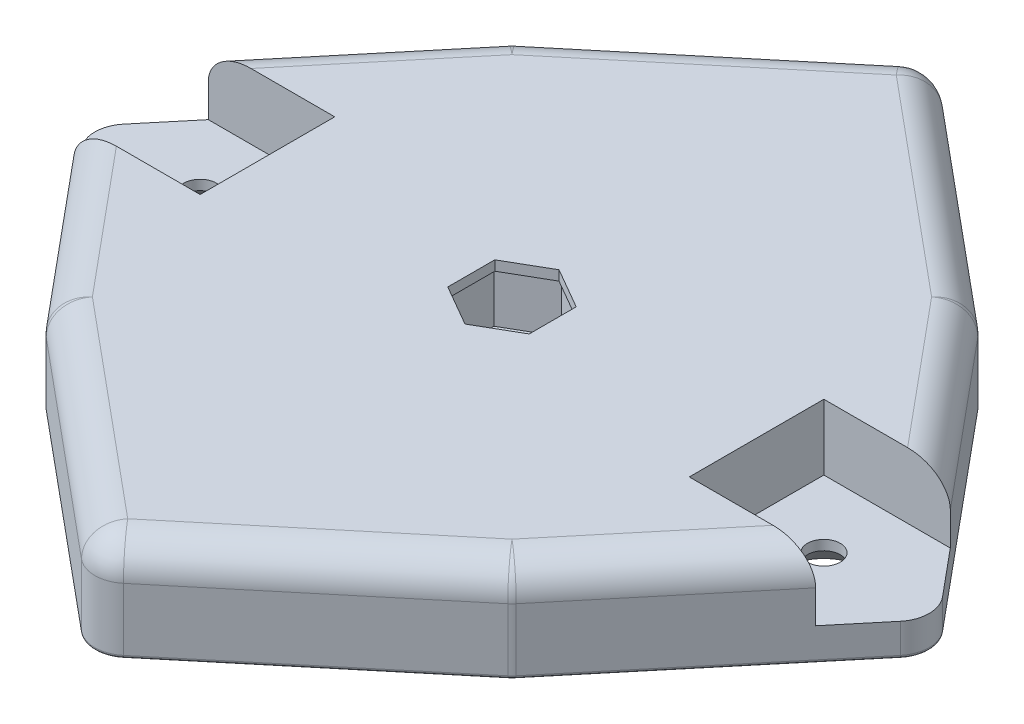
SolidWorks part; units mm, degrees
ref_plane "Front" through (0, 0, 0) normal (0, 0, 1) x (1, 0, 0)
ref_plane "Top" through (0, 0, 0) normal (0, 1, 0) x (1, 0, 0)
ref_plane "Right" through (0, 0, 0) normal (1, 0, 0) x (0, 0, -1)
sketch "Esquisse1" plane through (0, 0, 0) normal (0, 1, 0) x (1, 0, 0)
  line L0 (-47.5, 0) -> (47.5, 0) construction
  line L5 (-65.0329, 0) -> (0, -78.1935)
  line L6 (-65.0329, 0) -> (0, 78.1935)
  line L7 (0, -78.1935) -> (65.0329, 0)
  line L8 (0, 78.1935) -> (65.0329, 0)
  circle A0 centre (0, 0) radius 4.5
  circle A1 centre (-47.5, 0) radius 2.5
  circle A2 centre (47.5, 0) radius 2.5
  point P48 (0, 0)
  dimension "D1" = 9
  dimension "D3" = 5
  dimension "D5" = 100
  dimension "D2" = 100
  dimension "D4" = 95
  dimension "D6" = 100.5
extrude "Boss.-Extru.1" add sketch "Esquisse1" along normal blind 15
sketch "Esquisse2" plane through (0, 15, 0) normal (0, 1, 0) x (1, 0, 0)
  line L0 (0, 65.0329) -> (-78.1935, 0)
  line L1 (-78.1935, 0) -> (0, -65.0329)
  line L2 (0, -65.0329) -> (78.1935, 0)
  line L3 (78.1935, 0) -> (0, 65.0329)
  line L4 (-78.1935, 0) -> (78.1935, 0) construction
  line L5 (65.0329, 0) -> (0, 78.1935) construction
  dimension "D1" = 100.5
extrude "Enlèv. mat.-Extru.1" cut sketch "Esquisse2" against normal through all flip side to cut
fillet "Congé1" radius 5 8 edges at (0, 7.5, 65.0329) (-35.5043, 7.5, 35.5043) (-35.5043, 7.5, -35.5043) (0, 7.5, -65.0329) (35.5043, 7.5, -35.5043) (65.0329, 7.5, 0) (35.5043, 7.5, 35.5043) (-65.0329, 7.5, 0)
sketch "Esquisse3" plane through (0, 15, 0) normal (0, 1, 0) x (1, 0, 0)
  line L0 (0, -50) -> (0, 50) construction
  line L1 (-63.5296, 10.25) -> (-37.25, 10.25)
  line L3 (-63.5296, -10.25) -> (-37.25, -10.25)
  line L4 (-37.25, 10.25) -> (-37.25, -10.25)
  line L5 (-47.5, -10.25) -> (-47.5, 10.25) construction
  line L6 (-63.5296, 0) -> (-37.25, 0) construction
  line L8 (-63.5296, 10.25) -> (-63.5296, -10.25)
  line L9 (63.5296, 10.25) -> (63.5296, -10.25)
  line L27 (37.25, 10.25) -> (37.25, -10.25)
  line L28 (63.5296, -10.25) -> (37.25, -10.25)
  line L29 (63.5296, 10.25) -> (37.25, 10.25)
  circle A3 centre (-47.5, 0) radius 2.5 construction
  arc A4 (-62.3738, 3.1972) -> (-62.3738, -3.1972) centre (-58.5296, 0) ccw construction
  point P0 (0, 0)
  point P49 (47.5, 0)
  point P91 (-47.5, 0)
  dimension "D2" = 20.5
  dimension "D3" = 10.25
sketch "Esquisse4" plane through (0, 15, 0) normal (0, 1, 0) x (1, 0, 0)
  line L1 (6.5, 3.7528) -> (0, 7.5056)
  line L2 (0, 7.5056) -> (-6.5, 3.7528)
  line L3 (-6.5, 3.7528) -> (-6.5, -3.7528)
  line L4 (-6.5, -3.7528) -> (0, -7.5056)
  line L5 (0, -7.5056) -> (6.5, -3.7528)
  line L6 (6.5, -3.7528) -> (6.5, 3.7528)
  circle A0 centre (0, 0) radius 6.5 construction
  dimension "D1" = 13
extrude "Enlèv. mat.-Extru.2" cut sketch "Esquisse4" against normal blind 9
extrude "Enlèv. mat.-Extru.3" cut sketch "Esquisse3" against normal offset from surface (10 mm away) 5 up to face at (-47.5, 0, 2.5)
fillet "Congé2" radius 5 14 edges at (46.1531, 15, -22.7005) (35.4894, 15, -35.4894) (19.1741, 15, -49.0859) (0, 15, -63.5296) (-19.1741, 15, -49.0859) (-35.4894, 15, -35.4894) (46.1531, 15, 22.7005) (35.4894, 15, 35.4894) (19.1741, 15, 49.0859) (0, 15, 63.5296) (-19.1741, 15, 49.0859) (-35.4894, 15, 35.4894) (-46.1531, 15, -22.7005) (-46.1531, 15, 22.7005)
fillet "Congé3" radius 0.5 16 edges at (-63.5296, 0, 0) (-49.0859, 0, -19.1741) (-35.4894, 0, -35.4894) (-19.1741, 0, -49.0859) (0, 0, -63.5296) (19.1741, 0, -49.0859) (35.4894, 0, -35.4894) (49.0859, 0, -19.1741) (63.5296, 0, 0) (49.0859, 0, 19.1741) (35.4894, 0, 35.4894) (19.1741, 0, 49.0859) (0, 0, 63.5296) (-19.1741, 0, 49.0859) (-35.4894, 0, 35.4894) (-49.0859, 0, 19.1741)
sketch "Esquisse5" plane through (0, 15, 0) normal (0, 1, 0) x (1, 0, 0)
  line L0 (6.5, 3.7528) -> (0, 7.5056) construction
  line L1 (6.2, 3.5796) -> (0, 7.1591)
  line L2 (0, 7.1591) -> (-6.2, 3.5796)
  line L3 (-6.2, 3.5796) -> (-6.2, -3.5796)
  line L4 (-6.2, -3.5796) -> (0, -7.1591)
  line L5 (0, -7.1591) -> (6.2, -3.5796)
  line L6 (6.2, -3.5796) -> (6.2, 3.5796)
  circle A0 centre (0, 0) radius 6.2 construction
  circle A1 centre (0, 0) radius 7.5056
  dimension "D1" = 0.3
extrude "Boss.-Extru.2" add sketch "Esquisse5" against normal blind 1.5
chamfer "Chanfrein1" distance 3.5 angle 45 2 edges at (47.5, 0, 2.5) (-47.5, 0, 2.5)
